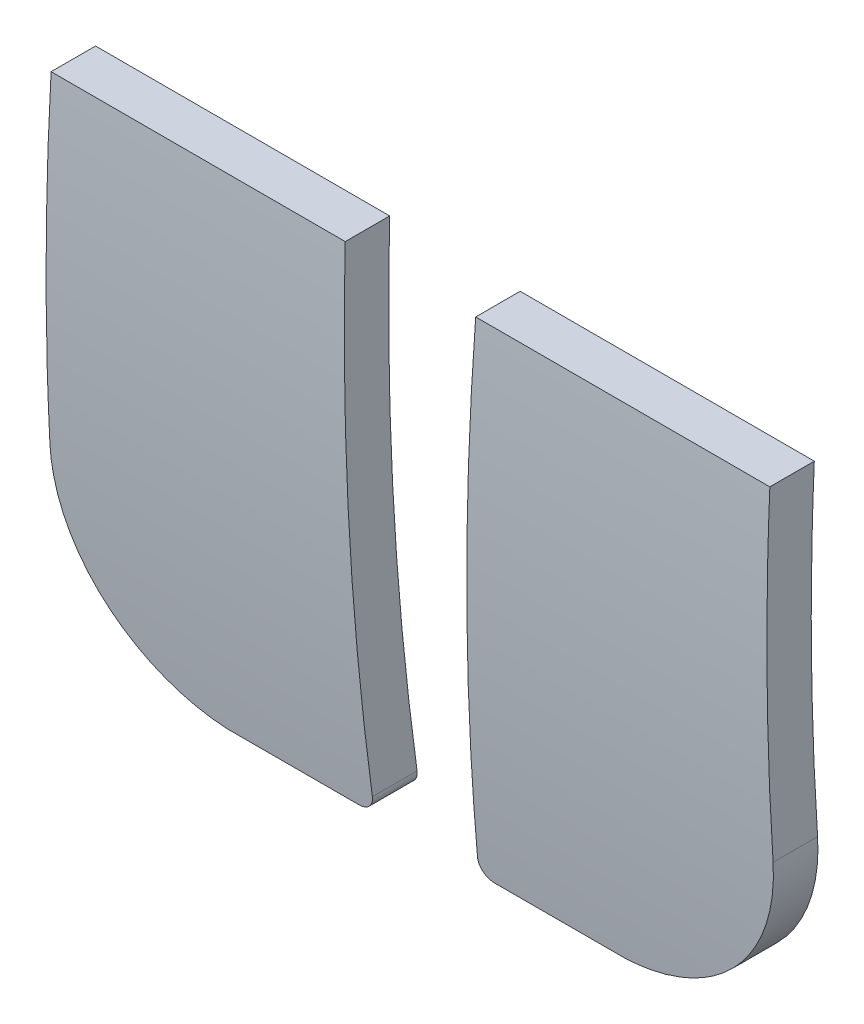
SolidWorks part; units mm, degrees
material "Thornel Mat VMA"
ref_plane "Front Plane" through (0, 0, 0) normal (0, 0, 1) x (1, 0, 0)
ref_plane "Top Plane" through (0, 0, 0) normal (0, 1, 0) x (1, 0, 0)
ref_plane "Right Plane" through (0, 0, 0) normal (1, 0, 0) x (0, 0, -1)
sketch "Sketch1" plane through (0, 0, 0) normal (0, 0, 1) x (1, 0, 0)
  line L0 (517.6644, 508.2863) -> (517.5204, 484.9114)
  line L1 (527.267, 474.5237) -> (535.2316, 474.5237)
  line L2 (536.1404, 475.4567) -> (534.7673, 527.6428)
  line L3 (543.8507, 527.6428) -> (542.4776, 475.4567)
  line L4 (543.3864, 474.5237) -> (551.351, 474.5237)
  line L5 (561.0975, 484.9114) -> (560.9536, 508.2863)
  line L6 (534.9347, 601.751) -> (514.3433, 601.751)
  line L7 (513.8907, 601.2538) -> (517.2171, 565.9502)
  line L8 (534.9347, 601.751) -> (535.9822, 601.751)
  line L9 (560.9536, 508.2863) -> (560.7342, 556.8701)
  line L10 (543.6833, 601.7663) -> (542.6219, 601.7663)
  line L11 (536.3021, 582.5059) -> (536.4364, 601.2786)
  line L12 (542.1677, 601.2938) -> (542.3021, 582.5059)
  line L13 (517.8838, 556.8701) -> (517.6644, 508.2863)
  line L14 (561.4008, 565.9502) -> (564.7273, 601.2538)
  line L15 (564.2747, 601.751) -> (543.6833, 601.7663)
  arc A0 (517.5204, 484.9114) -> (527.267, 474.5237) centre (527.9252, 484.9077) ccw
  arc A1 (535.2316, 474.5237) -> (536.1404, 475.4567) centre (535.2316, 475.4328) ccw
  arc A2 (539.309, 532.4272) -> (534.7673, 527.6428) centre (539.3065, 527.8818) ccw
  arc A3 (543.8507, 527.6428) -> (539.309, 532.4272) centre (539.3115, 527.8818) ccw
  arc A4 (542.4776, 475.4567) -> (543.3864, 474.5237) centre (543.3864, 475.4328) ccw
  arc A5 (551.351, 474.5237) -> (561.0975, 484.9114) centre (550.6961, 484.9045) ccw
  arc A6 (536.4364, 601.2786) -> (535.9822, 601.751) centre (535.9822, 601.2965) ccw
  arc A7 (514.3433, 601.751) -> (513.8907, 601.2538) centre (514.3433, 601.2965) ccw
  arc A8 (517.8838, 556.8701) -> (517.2171, 565.9502) centre (407.8229, 553.3542) ccw
  arc A9 (542.6219, 601.7663) -> (542.1677, 601.2938) centre (542.6219, 601.3117) ccw
  arc A10 (536.3021, 582.5059) -> (542.3021, 582.5059) centre (539.3021, 582.5059) ccw
  arc A11 (561.4008, 565.9502) -> (560.7342, 556.8701) centre (670.7951, 553.3542) ccw
  arc A12 (564.7273, 601.2538) -> (564.2747, 601.751) centre (564.2747, 601.2965) ccw
extrude "Boss-Extrude1" add sketch "Sketch1" along normal blind 111
sketch "Sketch3" plane through (563.2372, 2.5433, 0) normal (1, 0.0045, 0) x (0, 0, -1)
  line L0 (-54.1524, 472.0293) -> (-56.8476, 472.0293)
  line L1 (-57.8304, 502.1481) -> (-56.4634, 528.137)
  line L2 (-64.6908, 599.2552) -> (-67.3855, 599.2552)
  arc A0 (-64.6908, 599.2552) -> (-55.5331, 554.3491) centre (208.6561, 631.612) ccw
  arc A1 (-53.2994, 519.8266) -> (-55.5331, 554.3491) centre (-131.6409, 532.0912) ccw
  arc A2 (-53.2994, 519.8266) -> (-54.1524, 472.0293) centre (119.0519, 492.8444) ccw
  arc A3 (-57.8304, 502.1481) -> (-56.8476, 472.0293) centre (119.0519, 492.8444) ccw
  arc A4 (-56.4634, 528.137) -> (-58.0685, 548.0409) centre (-131.6409, 532.0912) ccw
  arc A5 (-64.8743, 582.3466) -> (-58.0685, 548.0409) centre (910.6264, 758.0432) ccw
  arc A6 (-67.3855, 599.2552) -> (-64.8743, 582.3466) centre (208.6561, 631.612) ccw
extrude "Cut-Extrude1" cut sketch "Sketch3" against normal blind 135 and the other way blind 87 flip side to cut
sketch "Sketch4" plane through (0, 0, 0) normal (0, 0, 1) x (1, 0, 0)
  line L0 (531.2493, 474.5237) -> (547.3687, 474.5237) construction
  line L1 (527.267, 474.5237) -> (535.2316, 474.5237) construction
  line L2 (543.3864, 474.5237) -> (551.351, 474.5237) construction
  line L3 (539.309, 474.5237) -> (539.309, 569.0237) construction
  line L4 (539.309, 569.0237) -> (526.259, 569.0237) construction
  line L5 (539.309, 569.0237) -> (552.359, 569.0237) construction
  line L6 (526.259, 569.0237) -> (526.259, 568.3128) construction
  line L7 (552.359, 569.0237) -> (552.359, 578.2415) construction
  line L9 (525.21, 573.0737) -> (527.3079, 573.0737)
  line L10 (551.31, 573.0737) -> (553.4079, 573.0737)
  arc A0 (523.2245, 572.4141) -> (529.2935, 572.4141) centre (526.259, 569.0237) ccw
  arc A1 (549.3245, 572.4141) -> (555.3935, 572.4141) centre (552.359, 569.0237) ccw
  arc A2 (525.21, 573.0737) -> (523.2245, 572.4141) centre (524.5562, 571.7237) ccw
  arc A3 (527.3079, 573.0737) -> (529.2935, 572.4141) centre (527.9618, 571.7237) cw
  arc A4 (553.4079, 573.0737) -> (555.3935, 572.4141) centre (554.0618, 571.7237) cw
  arc A5 (551.31, 573.0737) -> (549.3245, 572.4141) centre (550.6562, 571.7237) ccw
  dimension "D4" = 9.1
  dimension "D5" = 9.1
  dimension "D6" = 3
  dimension "D1" = 94.5
  dimension "D2" = 13.05
  dimension "D3" = 13.05
  dimension "D7" = 1.7028
  dimension "D8" = 2.7
  dimension "D9" = 4.05
extrude "Cut-Extrude2" cut sketch "Sketch4" along normal blind 130 contours A1 A4 L10 A5 | A3 A0 A2 L9
ref_plane "Plane1" through (-0.0508, 11.2606, -55.2188) normal (-0.0009, 0.1998, -0.9798) x (-1, -0.0002, 0.0009)
ref_plane "Plane2" through (539.309, 0, 0) normal (-1, 0, 0) x (0, 0, 1)
ref_plane "Düzlem1" through (539.309, 0, 0) normal (-1, 0, 0) x (0, 0, 1)
sketch "Çizim1" plane through (0, 0, 0) normal (0, 0, 1) x (1, 0, 0)
  line L0 (517.641, 635.3179) -> (477.3268, 635.3179)
  line L1 (517.641, 504.4906) -> (580.2018, 504.4906)
  line L3 (517.641, 635.3179) -> (580.2018, 635.3179)
  line L4 (580.2018, 504.4906) -> (580.2018, 635.3179)
  line L5 (477.3268, 635.3179) -> (477.3268, 504.4906)
  line L6 (477.3268, 504.4906) -> (517.641, 504.4906)
extrude "Kes-Ekstrüzyon2" cut sketch "Çizim1" against normal mid plane 210
